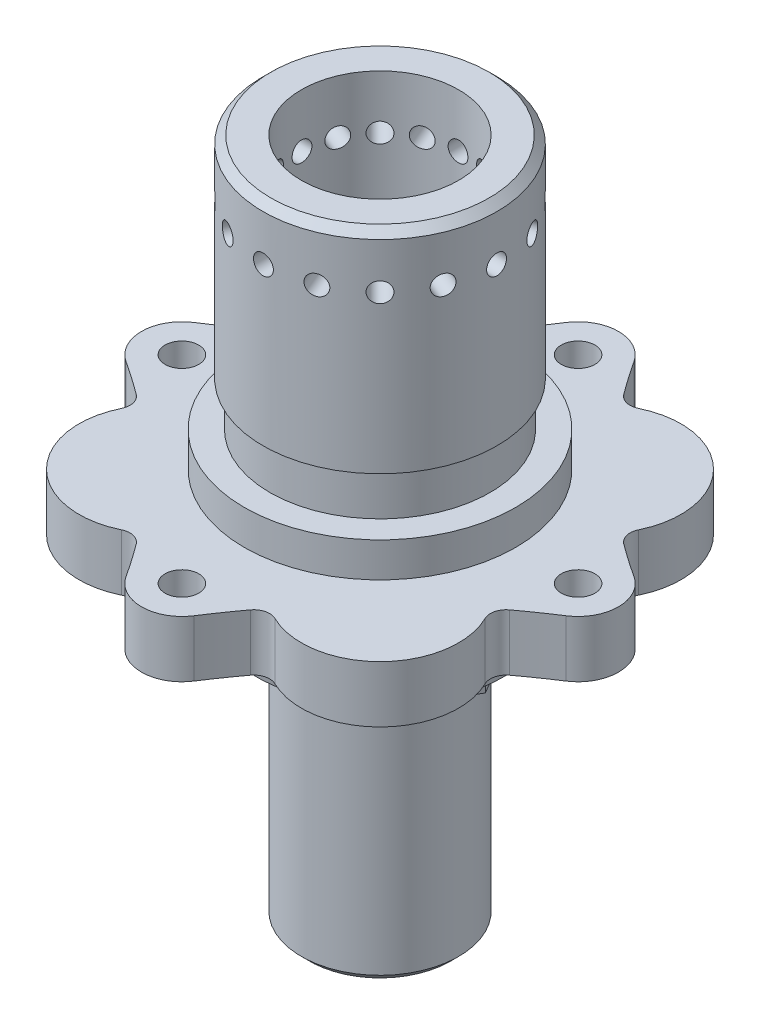
SolidWorks part; units mm, degrees
material "6061-T6 (SS)"
ref_plane "X-Y Datum" through (0, 0, 0) normal (0, 0, 1) x (1, 0, 0)
ref_plane "X-Z Datum" through (0, 0, 0) normal (0, 1, 0) x (1, 0, 0)
ref_plane "Y-Z Datum" through (0, 0, 0) normal (1, 0, 0) x (0, 0, -1)
sketch "Sketch1" plane through (0, 0, 0) normal (1, 0, 0) x (0, 0, -1)
  line L0 (0, 0) -> (-50000, 0) construction
  line L1 (0, 0) -> (0, 50000) construction
  line L2 (0, 0) -> (-27.2547, 0)
  line L3 (-27.2547, 0) -> (-25.0825, -12.319)
  line L4 (-25.0825, -12.319) -> (-25.0825, -17.0815)
  line L5 (-25.0825, -17.0815) -> (-15.875, -17.0815)
  line L8 (0, -67.4624) -> (0, 0)
  line L9 (0, -67.4624) -> (-14.2875, -67.4624)
  line L10 (-15.875, -17.0815) -> (-15.875, -65.8749)
  line L11 (-14.2875, -67.4624) -> (-15.875, -65.8749)
  dimension "D1" = 12.319
  dimension "D2" = 4.7625
  dimension "D3" = 50.3809
  dimension "D4" = 50.165
  dimension "D5" = 45
  dimension "D6" = 80
  dimension "D7" = 31.75
  dimension "D8" = 1.5875
sketch "Sketch2" plane through (0, 0, 0) normal (1, 0, 0) x (0, 0, -1)
  line L0 (0, 0) -> (-52.5, 0)
  line L1 (200000, 0) -> (-250000, 0) construction
  line L2 (-52.5, 0) -> (-52.5, 11.43)
  line L3 (-52.5, 11.43) -> (-27.4096, 11.43)
  line L4 (-27.4096, 11.43) -> (-27.4096, 18.43)
  line L5 (-27.4096, 18.43) -> (-22.225, 18.43)
  line L6 (-22.225, 18.43) -> (-22.225, 27.305)
  line L7 (-22.225, 27.305) -> (-23.6195, 27.305)
  line L10 (0, -200000) -> (0, 250000) construction
  line L11 (0, 69.85) -> (0, 0)
  line L15 (0, 69.85) -> (-22.032, 69.85)
  line L16 (-22.032, 69.85) -> (-23.6195, 68.2625)
  line L17 (-23.6195, 68.2625) -> (-23.6195, 27.305)
  line L18 (0, 0) -> (-50000, 0) construction
  line L19 (0, 0) -> (0, 50000) construction
  line L20 (0, 0) -> (0, -31242.0183) construction
  dimension "D1" = 11.43
  dimension "D2" = 58.42
  dimension "D3" = 47.2389
  dimension "D4" = 1.5875
  dimension "D5" = 45
  dimension "D6" = 54.8192
  dimension "D7" = 105
  dimension "D8" = 7
  dimension "D9" = 40.9575
  dimension "D10" = 44.45
revolve "Bearing Shaft/Flange Support" add sketch "Sketch1" angle 360 about L1
revolve "Drive Pin Support" add sketch "Sketch2" angle 360 about L19
sketch "Sketch5" plane through (0, 0, 0) normal (1, 0, 0) x (0, 0, -1)
  line L0 (0, 69.85) -> (15.875, 69.85)
  line L1 (22.032, 69.85) -> (-22.032, 69.85) construction
  line L4 (15.875, -9.525) -> (0, -9.525)
  line L5 (0, -9.525) -> (0, 69.85)
  line L6 (0, 0) -> (-50000, 0) construction
  line L7 (15.875, -9.525) -> (15.875, 69.85)
  line L8 (0, 0) -> (0, -50000) construction
  dimension "D1" = 79.375
  dimension "D4" = 31.75
revolve "Center Mass Removal" cut sketch "Sketch5" angle 360 about L8
hole_wizard "Drive Pin Holes" positions "Sketch6" profile "Sketch7" tap size "M8x1.25" standard "ANSI Metric" end condition through all
sketch "Sketch6" plane through (0, 0, 0) normal (0, -1, 0) x (-1, 0, 0)
  circle A0 centre (0, 0) radius 40 construction
  point P0 (0, -40)
  dimension "D1" = 80
sketch "Sketch7" plane through (0, 0, 40) normal (1, 0, 0) x (0, 0, -1)
  line L0 (0, 0) -> (0, 69.85)
  line L1 (0, 69.85) -> (3.4, 69.85)
  line L2 (3.4, 69.85) -> (3.4, 0)
  line L5 (3.4, 0) -> (0, 0)
  line L11 (0, -6.35) -> (0, 107.95) construction
  dimension "Thru Tap Drill Dia." = 6.8
  dimension "Thru Tap Drill Depth" = 69.85
cosmetic thread "Hole Thread1" parameters "D2"=8
pattern_circular "Drive Pin Holes Pattern" count 4 over 360 about axis through (0, 0, 0) along (0, 1, 0) of "Drive Pin Holes"
cosmetic thread "Hole Thread2" parameters "D2"=8
cosmetic thread "Hole Thread3" parameters "D2"=8
cosmetic thread "Hole Thread4" parameters "D2"=8
sketch "Sketch8" plane through (0, 0, 0) normal (0, -1, 0) x (1, 0, 0)
  line L0 (0, 0) -> (-64.0279, 64.0279) construction
  line L1 (0, 0) -> (0, 72.7145) construction
  arc A0 (6.8518, 44.4362) -> (-6.8518, 44.4362) centre (0, 40) ccw
  arc A1 (6.8518, 44.4362) -> (13.2749, 35.4052) centre (113.4583, 113.4583) ccw
  arc A2 (44.4362, -6.8518) -> (44.4362, 6.8518) centre (40, 0) ccw
  arc A3 (44.4362, -6.8518) -> (44.4362, 6.8518) centre (40, 0) ccw
  arc A5 (44.4362, -6.8518) -> (35.4052, -13.2749) centre (113.4583, -113.4583) ccw
  circle A7 centre (0, 40) radius 3.4 construction
  circle A8 centre (0, 0) radius 52.5 construction
  circle A9 centre (0, 0) radius 40 construction
  arc A10 (-6.8518, -44.4362) -> (6.8518, -44.4362) centre (0, -40) ccw
  arc A11 (-6.8518, -44.4362) -> (6.8518, -44.4362) centre (0, -40) ccw
  arc A13 (-44.4362, 6.8518) -> (-44.4362, -6.8518) centre (-40, 0) ccw
  arc A14 (-44.4362, 6.8518) -> (-44.4362, -6.8518) centre (-40, 0) ccw
  arc A15 (-44.4362, 6.8518) -> (-35.4052, 13.2749) centre (-113.4583, 113.4583) ccw
  arc A16 (6.8518, 44.4362) -> (-6.8518, 44.4362) centre (0, 40) ccw
  circle A17 centre (0, 0) radius 52.5
  arc A18 (-6.8518, -44.4362) -> (-13.2749, -35.4052) centre (-113.4583, -113.4583) ccw
  arc A19 (-169.6965, 0.4112) -> (0.4112, -169.6965) centre (-113.4583, -113.4583) ccw [skipped]
  arc A20 (-13.2749, 35.4052) -> (-35.4052, 13.2749) centre (-22.4506, 22.4506) ccw
  arc A21 (-13.2749, 35.4052) -> (-6.8518, 44.4362) centre (-113.4583, 113.4583) ccw
  arc A22 (35.4052, 13.2749) -> (13.2749, 35.4052) centre (22.4506, 22.4506) ccw
  arc A23 (13.2749, -35.4052) -> (35.4052, -13.2749) centre (22.4506, -22.4506) ccw
  arc A24 (-35.4052, -13.2749) -> (-13.2749, -35.4052) centre (-22.4506, -22.4506) ccw
  arc A25 (35.4052, 13.2749) -> (44.4362, 6.8518) centre (113.4583, 113.4583) ccw
  arc A26 (13.2749, -35.4052) -> (6.8518, -44.4362) centre (113.4583, -113.4583) ccw
  arc A27 (-35.4052, -13.2749) -> (-44.4362, -6.8518) centre (-113.4583, -113.4583) ccw
  point P49 (0, 0)
  circle M10 centre (0, 0) radius 52.5
  dimension "D1" = 4.7625
  dimension "D2" = 45
  dimension "D3" = 254
  dimension "D4" = 80
  dimension "D6" = 31.75
  dimension "D7" = 31.75
  dimension "D5" = 4
  dimension "D8" = 4
extrude "Flange Support Cut" cut sketch "Sketch8" against normal up to next contours A10 A18 A13 A15 A0 A1 A2 A5 M10
sketch "Sketch10" plane through (0, -17.0815, 0) normal (0, -1, 0) x (1, 0, 0)
  line L0 (0, 0) -> (0, 50000) construction
  line L1 (10.6319, -18.415) -> (21.2638, 0)
  line L2 (21.2638, 0) -> (10.6319, 18.415)
  line L3 (10.6319, 18.415) -> (-10.6319, 18.415)
  line L4 (-10.6319, 18.415) -> (-21.2638, 0)
  line L5 (-21.2638, 0) -> (-10.6319, -18.415)
  line L6 (-10.6319, -18.415) -> (10.6319, -18.415)
  line L7 (0, 0) -> (50000, 0) construction
  circle A0 centre (0, 0) radius 18.415 construction
  circle A1 centre (0, 0) radius 25.0825 construction
  circle A2 centre (0, 0) radius 25.0825
  point P17 (0, 18.415)
  dimension "D1" = 36.83
extrude "Brake Hat Hex" cut sketch "Sketch10" against normal blind 4.7625
sketch "Sketch11" plane through (0, -67.4624, 0) normal (0, -1, 0) x (1, 0, 0)
  circle A25 centre (0, 0) radius 9.525 construction
  circle A26 centre (0, 9.525) radius 3.175
  circle A27 centre (8.2489, 4.7625) radius 3.175
  circle A28 centre (8.2489, -4.7625) radius 3.175
  circle A29 centre (0, -9.525) radius 3.175
  circle A30 centre (-8.2489, -4.7625) radius 3.175
  circle A31 centre (-8.2489, 4.7625) radius 3.175
  dimension "D1" = 19.05
  dimension "D2" = 6.35
  dimension "D3" = 6
hole_wizard "M10 Clearance Hole1" positions "Sketch12" profile "Sketch13" hole size "M10" standard "ANSI Metric" end condition through all
sketch "Sketch12" plane through (0, -67.4624, 0) normal (0, -1, 0) x (-1, 0, 0)
  point P0 (0, 0)
sketch "Sketch13" plane through (0, -67.4624, 0) normal (1, 0, 0) x (0, 0, -1)
  line L0 (0, 0) -> (0, 137.3124)
  line L1 (0, 137.3124) -> (5.5, 137.3124)
  line L2 (5.5, 137.3124) -> (5.5, 0)
  line L5 (5.5, 0) -> (0, 0)
  line L11 (0, -6.35) -> (0, 107.95) construction
  dimension "Thru Hole Dia." = 11
  dimension "Thru Hole Depth" = 137.3124
fillet "Brake Hat Fillet" [suppressed] radius 3.175
fillet "Hub Fillet" [suppressed] radius 0.7937
sketch "Sketch14" plane through (0, 0, 0) normal (1, 0, 0) x (0, 0, -1)
  line L0 (22.032, 69.85) -> (-22.032, 69.85) construction
  line L1 (0, 0) -> (-50000, 0) construction
  line L2 (0, 0) -> (0, -50000) construction
  circle A0 centre (0, 59.05) radius 2
  dimension "D2" = 4
  dimension "D1" = 10.8
extrude "Pin Holes" cut sketch "Sketch14" against normal through all
pattern_circular "Pin Hole Pattern" count 16 over 360 about axis through (0, 0, 0) along (0, -1, 0) of "Pin Holes"
chamfer "Floral Pattern Chamfer" [suppressed] distance 3.175 angle 45
sketch3d "3DSketch2"
  line L0 (0, 0, 0) -> (0, 0, -205.74)
  line L1 (0, 0, -205.74) -> (25.4, 0, -205.74)
  line L2 (0, 0, -205.74) -> (0, -25.4, -205.74)
  dimension "D1" = 25.4
  dimension "D2" = 25.4
  dimension "D3" = 205.74
extrude "Tripod Pins" [suppressed] cut sketch "Sketch11" against normal blind 12.7
fillet "Flange Fillet" [suppressed] radius 1.27
sketch "Sketch15" plane through (0, 0, 0) normal (0, -1, 0) x (1, 0, 0)
  circle A0 centre (0, 0) radius 40 construction
  dimension "D1" = 80
thread "Thread1" [suppressed] pitch 2.1167 start angle 0, offset 0.3048, length 0, pitch 2.1167, diameter 47.625
ref_plane "Plane1" through (-23.8125, 70.1548, 0) normal (0, 0, 1) x (-1, 0, 0)
sketch "Thread Profile1" plane through (-23.8125, 70.1548, 0) normal (0, 0, 1) x (-1, 0, 0)
  line L0 (0, 0) -> (0, 2.1167) construction
  line L11 (0, 0) -> (0, 1.8521)
  line L12 (0, 1.8521) -> (-1.1457, 1.1906)
  line L13 (-1.1457, 1.1906) -> (-1.1457, 0.6615)
  line L15 (-1.1457, 0.6615) -> (0, 0)
  line L17 (-1.1457, 0.926) -> (0, 0.926) construction
  point P2 (0, 0)
  dimension "Pitch" = 2.1167
  dimension "Profile_Angle" = 60
  dimension "Profile_Land" = 0.5292
  dimension "Profile_Height" = 1.1457
fillet "Fillet1" radius 3.175 8 edges at (-13.2749, 5.715, 35.4052) (-35.4052, 5.715, 13.2749) (-35.4052, 5.715, -13.2749) (-13.2749, 5.715, -35.4052) (13.2749, 5.715, -35.4052) (35.4052, 5.715, -13.2749) (35.4052, 5.715, 13.2749) (13.2749, 5.715, 35.4052)
